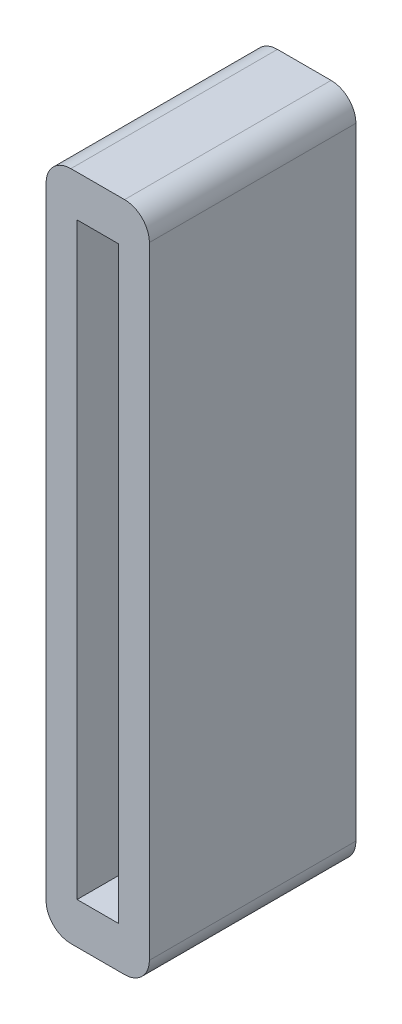
SolidWorks part; units mm, degrees
material "Copper"
ref_plane "Front Plane" through (0, 0, 0) normal (0, 0, 1) x (1, 0, 0)
ref_plane "Top Plane" through (0, 0, 0) normal (0, 1, 0) x (1, 0, 0)
ref_plane "Right Plane" through (0, 0, 0) normal (1, 0, 0) x (0, 0, -1)
sketch "Sketch1" plane through (0, 0, 0) normal (0, 0, 1) x (1, 0, 0)
  line L1 (-2, 28.5) -> (2, 28.5)
  line L2 (-2, 28.5) -> (-2, -28.5)
  line L3 (-2, -28.5) -> (2, -28.5)
  line L4 (2, 28.5) -> (2, -28.5)
  line L5 (-2, 28.5) -> (2, -28.5) construction
  line L6 (-2, -28.5) -> (2, 28.5) construction
  line L7 (-2.6, 32.5) -> (2.6, 32.5)
  line L8 (-5, 30.1) -> (-5, -30.1)
  line L9 (-2.6, -32.5) -> (2.6, -32.5)
  line L10 (5, 30.1) -> (5, -30.1)
  line L11 (-5, 32.5) -> (5, -32.5) construction
  line L12 (-5, -32.5) -> (5, 32.5) construction
  arc A0 (5, 30.1) -> (2.6, 32.5) centre (2.6, 30.1) ccw
  arc A1 (-2.6, 32.5) -> (-5, 30.1) centre (-2.6, 30.1) ccw
  arc A2 (5, -30.1) -> (2.6, -32.5) centre (2.6, -30.1) cw
  arc A3 (-5, -30.1) -> (-2.6, -32.5) centre (-2.6, -30.1) ccw
  point P0 (0, 0)
  point P6 (0, 0)
  dimension "D5" = 2.4
  dimension "D1" = 4
  dimension "D2" = 57
  dimension "D3" = 65
  dimension "D4" = 10
extrude "Boss-Extrude1" add sketch "Sketch1" along normal mid plane 20
